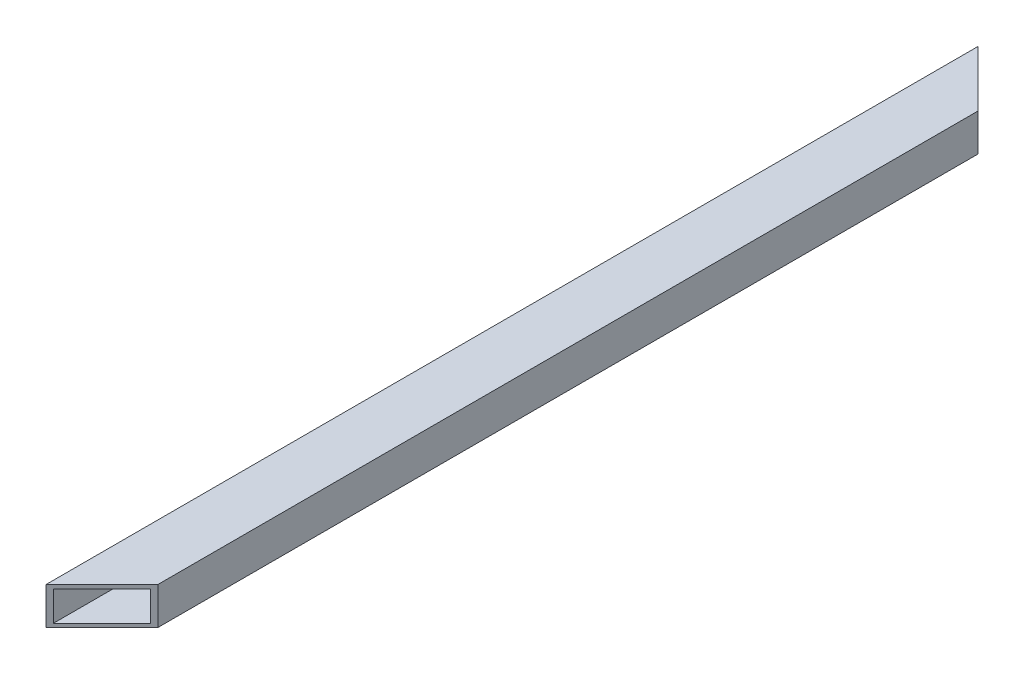
SolidWorks part; units mm, degrees
ref_plane "Piano frontale" through (0, 0, 0) normal (0, 0, 1) x (1, 0, 0)
ref_plane "Piano superiore" through (0, 0, 0) normal (0, 1, 0) x (1, 0, 0)
ref_plane "Piano destro" through (0, 0, 0) normal (1, 0, 0) x (0, 0, -1)
sketch "Schizzo1" plane through (0, 0, 0) normal (0, 0, 1) x (1, 0, 0)
  line L1 (13, -8) -> (-13, -8)
  line L2 (13, -8) -> (13, 8)
  line L3 (13, 8) -> (-13, 8)
  line L4 (-13, -8) -> (-13, 8)
  line L5 (13, -8) -> (-13, 8) construction
  line L6 (13, 8) -> (-13, -8) construction
  line L7 (15, -10) -> (-15, -10)
  line L8 (15, -10) -> (15, 10)
  line L9 (15, 10) -> (-15, 10)
  line L10 (-15, -10) -> (-15, 10)
  line L11 (15, -10) -> (-15, 10) construction
  line L12 (15, 10) -> (-15, -10) construction
  point P0 (0, 0)
  point P6 (0, 0)
  point P11 (-15, 0)
  dimension "D1" = 20
  dimension "D2" = 30
  dimension "D3" = 2
  dimension "D4" = 2
extrude "Estrusione-Estrusione1" add sketch "Schizzo1" along normal blind 500
sketch "Schizzo2" plane through (0, 10, 0) normal (0, 1, 0) x (1, 0, 0)
  line L0 (-15, 0) -> (15, -30)
  line L1 (15, -500) -> (15, 0) construction
  line L2 (15, 0) -> (-15, 0) construction
  line L3 (-15, 0) -> (15, 0)
  line L4 (15, 0) -> (15, -30)
  line L5 (-15, -500) -> (15, -470)
  line L6 (15, -470) -> (15, -500)
  line L7 (15, -500) -> (-15, -500)
  dimension "D1" = 45
  dimension "D2" = 45
extrude "Taglio-Estrusione1" cut sketch "Schizzo2" against normal through all
